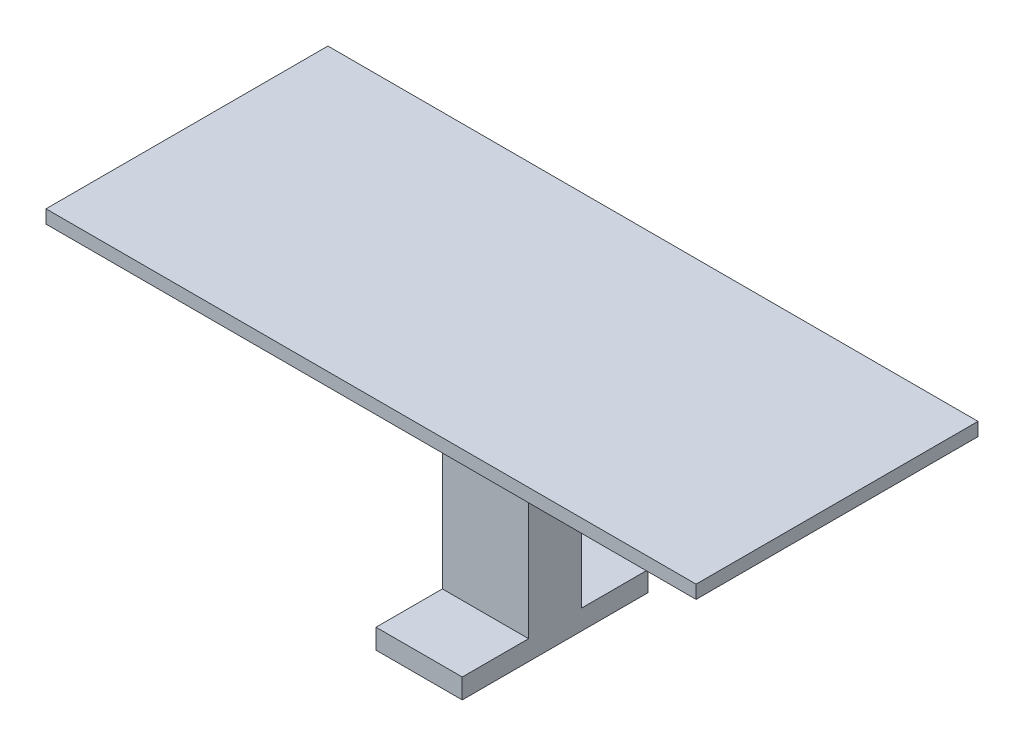
SolidWorks part; units mm, degrees
ref_plane "Front Plane" through (0, 0, 0) normal (0, 0, 1) x (1, 0, 0)
ref_plane "Top Plane" through (0, 0, 0) normal (0, 1, 0) x (1, 0, 0)
ref_plane "Right Plane" through (0, 0, 0) normal (1, 0, 0) x (0, 0, -1)
sketch "Sketch1" plane through (0, 0, 0) normal (0, 1, 0) x (1, 0, 0)
  line L1 (49, -21.25) -> (-49, -21.25)
  line L2 (49, -21.25) -> (49, 21.25)
  line L3 (49, 21.25) -> (-49, 21.25)
  line L4 (-49, -21.25) -> (-49, 21.25)
  line L5 (49, -21.25) -> (-49, 21.25) construction
  line L6 (49, 21.25) -> (-49, -21.25) construction
  point P0 (0, 0)
  dimension "D1" = 98
  dimension "D2" = 42.5
extrude "Boss-Extrude1" add sketch "Sketch1" along normal blind 2
sketch "Sketch2" plane through (0, 0, 0) normal (0, -1, 0) x (1, 0, 0)
  line L1 (6.5, -4) -> (-6.5, -4)
  line L2 (6.5, -4) -> (6.5, 4)
  line L3 (6.5, 4) -> (-6.5, 4)
  line L4 (-6.5, -4) -> (-6.5, 4)
  line L5 (6.5, -4) -> (-6.5, 4) construction
  line L6 (6.5, 4) -> (-6.5, -4) construction
  point P0 (0, 0)
  dimension "D1" = 13
  dimension "D2" = 8
extrude "Boss-Extrude2" add sketch "Sketch2" along normal blind 35
sketch "Sketch3" plane through (0, -35, 0) normal (0, -1, 0) x (1, 0, 0)
  line L1 (6.5, -14) -> (-6.5, -14)
  line L2 (6.5, -14) -> (6.5, 14)
  line L3 (6.5, 14) -> (-6.5, 14)
  line L4 (-6.5, -14) -> (-6.5, 14)
  line L5 (6.5, -14) -> (-6.5, 14) construction
  line L6 (6.5, 14) -> (-6.5, -14) construction
  point P0 (0, 0)
  dimension "D1" = 13
  dimension "D2" = 28
extrude "Boss-Extrude3" add sketch "Sketch3" along normal blind 3
